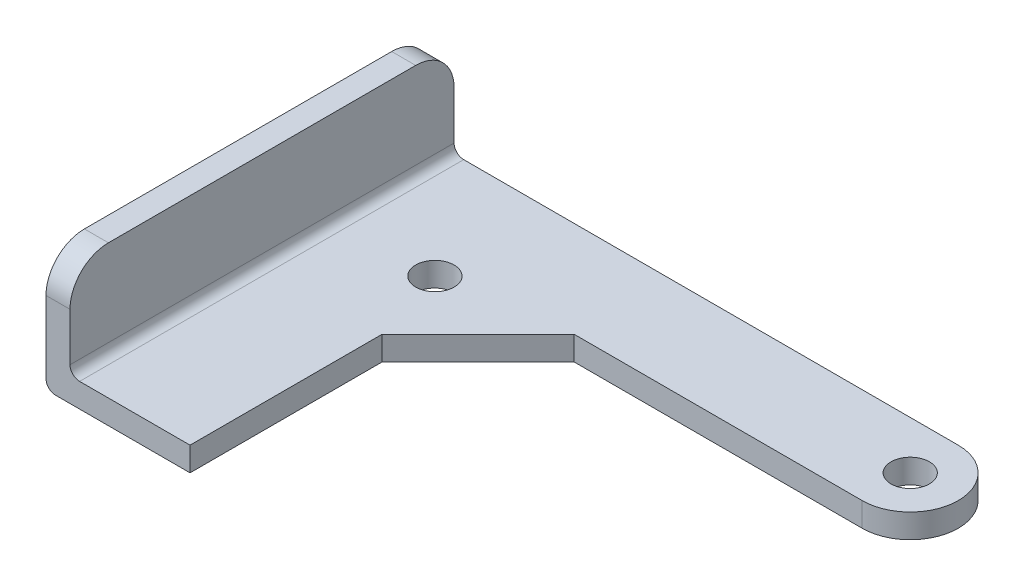
SolidWorks part; units mm, degrees
ref_plane "Front Plane" through (0, 0, 0) normal (0, 0, 1) x (1, 0, 0)
ref_plane "Top Plane" through (0, 0, 0) normal (0, 1, 0) x (1, 0, 0)
ref_plane "Right Plane" through (0, 0, 0) normal (1, 0, 0) x (0, 0, -1)
sketch "Sketch1" plane through (0, 0, 0) normal (0, 1, 0) x (1, 0, 0)
  line L0 (0, 0) -> (550, 0)
  line L1 (0, 0) -> (0, -400)
  line L2 (0, -400) -> (150, -400)
  line L3 (150, -400) -> (150, -200)
  line L4 (250, -100) -> (550, -100)
  line L5 (150, -200) -> (250, -100)
  arc A0 (550, 0) -> (550, -100) centre (550, -50) cw
  circle A1 centre (550, -50) radius 20
  circle A2 centre (125, -120) radius 20
  point P6 (150, -100)
  dimension "D4" = 40
  dimension "D1" = 400
  dimension "D2" = 400
  dimension "D3" = 50
  dimension "D5" = 150
  dimension "D6" = 100
  dimension "D7" = 45
  dimension "D8" = 25
  dimension "D9" = 120
extrude "Boss-Extrude1" add sketch "Sketch1" along normal mid plane 25
sketch "Sketch2" plane through (0, 12.5, 0) normal (0, 1, 0) x (1, 0, 0)
  line L0 (25, 0) -> (25, -400)
  line L1 (550, 0) -> (0, 0) construction
  line L2 (0, -400) -> (150, -400) construction
  line L3 (0, 0) -> (0, -400) construction
  line L4 (25, 0) -> (0, 0)
  line L5 (0, 0) -> (0, -400)
  line L6 (0, -400) -> (25, -400)
  dimension "D1" = 25
extrude "Boss-Extrude2" add sketch "Sketch2" along normal blind 100
sketch "Sketch3" plane through (0, 0, 0) normal (-1, 0, 0) x (0, 0, 1)
  line L0 (0, 72.5) -> (0, 112.5)
  line L1 (0, 112.5) -> (40, 112.5)
  line L2 (360, 112.5) -> (400, 112.5)
  line L3 (400, 112.5) -> (400, 72.5)
  line L4 (0, -12.5) -> (400, -12.5)
  line L5 (400, -12.5) -> (400, 112.5)
  line L6 (400, 112.5) -> (0, 112.5)
  line L7 (0, 112.5) -> (0, -12.5)
  line L10 (360, 112.5) -> (40, 112.5)
  line L12 (0, 112.5) -> (0, -12.5) construction
  arc A0 (400, 72.5) -> (360, 112.5) centre (360, 72.5) ccw
  arc A1 (40, 112.5) -> (0, 72.5) centre (40, 72.5) ccw
  circle A2 centre (40, 72.5) radius 7.94
  circle A3 centre (360, 72.5) radius 7.94
  line M8 (400, -12.5) -> (400, 112.5)
  line M9 (400, 112.5) -> (0, 112.5)
  line M10 (0, 112.5) -> (0, -12.5)
  dimension "D2" = 40
  dimension "D3" = 15.88
  dimension "D4" = 320
  dimension "D5" = 40
  dimension "D1" = 0
extrude "Cut-Extrude2" cut sketch "Sketch3" against normal through all contours A1 M9 M10 | A0 M8 M9
fillet "Fillet1" radius 10 2 edges at (25, 12.5, 200) (0, -12.5, 200)
